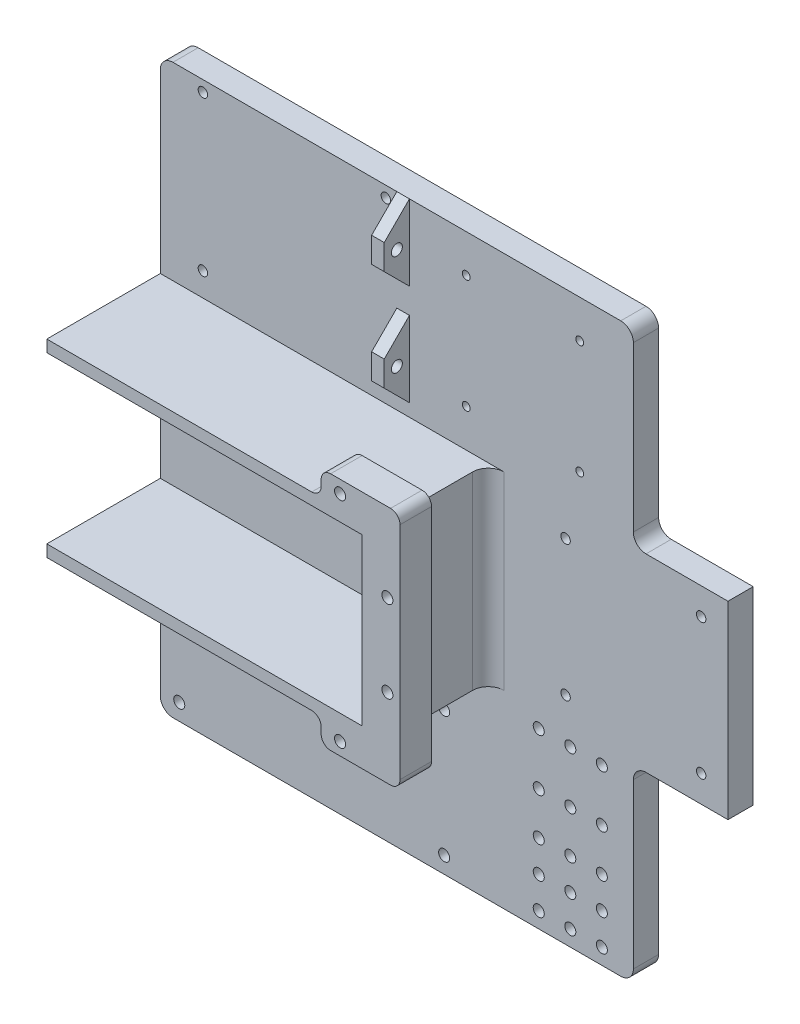
SolidWorks part; units mm, degrees
ref_plane "前视基准面" through (0, 0, 0) normal (0, 0, 1) x (1, 0, 0)
ref_plane "上视基准面" through (0, 0, 0) normal (0, 1, 0) x (1, 0, 0)
ref_plane "右视基准面" through (0, 0, 0) normal (1, 0, 0) x (0, 0, -1)
sketch "草图1" plane through (0, 0, 0) normal (0, 0, 1) x (1, 0, 0)
  line L1 (0, 0) -> (60, 0)
  line L2 (0, 0) -> (0, 60)
  line L3 (0, 60) -> (60, 60)
  line L4 (60, 0) -> (60, 60)
  dimension "D1" = 60
  dimension "D2" = 60
extrude "凸台-拉伸1" add sketch "草图1" along normal blind 8
sketch "草图2" plane through (0, 0, 0) normal (0, 0, -1) x (-1, 0, 0)
  line L0 (0, 0) -> (-60, 60)
  line L2 (-51.5, 8.5) -> (-8.5, 8.5)
  line L3 (-51.5, 8.5) -> (-51.5, 51.5)
  line L4 (-51.5, 51.5) -> (-8.5, 51.5)
  line L5 (-8.5, 8.5) -> (-8.5, 51.5)
  line L6 (-51.5, 8.5) -> (-8.5, 51.5) construction
  line L7 (-51.5, 51.5) -> (-8.5, 8.5) construction
  point P4 (-30, 30)
  dimension "D1" = 43
  dimension "D2" = 43
sketch "草图3" plane through (0, 0, 0) normal (0, 0, -1) x (-1, 0, 0)
  point P0 (-51.5, 51.5)
  point P3 (-8.5, 51.5)
  point P6 (-8.5, 8.5)
  point P9 (-51.5, 8.5)
hole_wizard "孔1" positions "草图3" profile "草图4" legacy end condition through all
sketch "草图4" plane through (51.5, 51.5, 0) normal (1, 0, 0) x (0, 1, 0)
  line L0 (0, 0) -> (0, 8)
  line L1 (0, 8) -> (1.5, 8)
  line L2 (1.5, 8) -> (1.5, 0)
  line L3 (1.5, 0) -> (0, 0)
  line L4 (0, 110) -> (0, -10) construction
  dimension "直径" = 3
  dimension "深度" = 8
sketch "草图5" plane through (0, 0, 0) normal (0, 0, -1) x (-1, 0, 0)
  point P0 (-51.5, 51.5)
  point P3 (-8.5, 51.5)
  point P6 (-8.5, 8.5)
  point P9 (-51.5, 8.5)
hole_wizard "孔2" positions "草图5" profile "草图6" legacy
sketch "草图6" plane through (51.5, 51.5, 0) normal (1, 0, 0) x (0, 1, 0)
  line L0 (0, 0) -> (0, 3)
  line L1 (0, 3) -> (2.5, 3)
  line L2 (2.5, 3) -> (2.5, 0)
  line L3 (2.5, 0) -> (0, 0)
  line L4 (0, 110) -> (0, -10) construction
  dimension "直径" = 5
  dimension "深度" = 3
sketch "草图8" plane through (0, 0, 8) normal (0, 0, 1) x (1, 0, 0)
  line L0 (60, 0) -> (60, 60) construction
  line L1 (60, -60) -> (-120, -60)
  line L2 (60, -60) -> (60, 120)
  line L3 (60, 120) -> (-120, 120)
  line L4 (-120, -60) -> (-120, 120)
  circle A0 centre (30, 30) radius 300
  dimension "D1" = 600
  dimension "D2" = 180
  dimension "D3" = 180
  dimension "D4" = 90
sketch "草图9" plane through (0, 0, 8) normal (0, 0, 1) x (1, 0, 0)
  line L1 (0, 60) -> (-25, 60)
  line L2 (0, 60) -> (0, 0)
  line L3 (0, 0) -> (-25, 0)
  line L4 (-25, 60) -> (-25, 0)
  dimension "D1" = 25
  dimension "D2" = 60
extrude "凸台-拉伸2" add sketch "草图9" against normal blind 8
sketch "草图10" plane through (0, 0, 8) normal (0, 0, 1) x (1, 0, 0)
  line L0 (-25, 0) -> (60, 0) construction
  line L1 (-20, 60) -> (-16, 60)
  line L2 (-20, 60) -> (-20, 0)
  line L3 (-20, 0) -> (-16, 0)
  line L4 (-16, 60) -> (-16, 0)
  line L5 (-25, 60) -> (-25, 0) construction
  dimension "D1" = 4
  dimension "D2" = 5
  dimension "D3" = 60
extrude "凸台-拉伸3" add sketch "草图10" along normal blind 20
fillet "圆角1" radius 5 1 edges at (-16, 30, 8)
sketch "草图11" plane through (0, 0, 8) normal (0, 0, 1) x (1, 0, 0)
  line L1 (-20, 60) -> (-120, 60)
  line L2 (-20, 60) -> (-20, 0)
  line L3 (-20, 0) -> (-120, 0)
  line L4 (-120, 60) -> (-120, 0)
  dimension "D1" = 100
  dimension "D2" = 60
extrude "凸台-拉伸4" add sketch "草图11" against normal blind 8
sketch "草图17" plane through (0, 0, 8) normal (0, 0, 1) x (1, 0, 0)
  line L1 (60, 60) -> (-120, 60)
  line L2 (60, 60) -> (60, 120)
  line L3 (60, 120) -> (-120, 120)
  line L4 (-120, 60) -> (-120, 120)
  line L5 (60, 0) -> (-120, 0)
  line L6 (60, 0) -> (60, -60)
  line L7 (60, -60) -> (-120, -60)
  line L8 (-120, 0) -> (-120, -60)
extrude "凸台-拉伸5" add sketch "草图17" against normal blind 8
sketch "草图12" plane through (0, 0, 8) normal (0, 0, 1) x (1, 0, 0)
  line L0 (-120, -60) -> (-120, 120) construction
  line L1 (-130, 120) -> (-45, 120)
  line L2 (-130, 120) -> (-130, 64)
  line L3 (-130, 64) -> (-45, 64)
  line L4 (-45, 120) -> (-45, 64)
  line L5 (-45, 92) -> (-130, 92)
  line L7 (-106.5, 116.5) -> (-48.5, 116.5)
  line L8 (-106.5, 116.5) -> (-106.5, 67.5)
  line L9 (-106.5, 67.5) -> (-48.5, 67.5)
  line L10 (-48.5, 116.5) -> (-48.5, 67.5)
  line L11 (60, 120) -> (-120, 120) construction
  point P8 (-120, 30)
  dimension "D1" = 56
  dimension "D2" = 85
  dimension "D3" = 3.5
  dimension "D4" = 3.5
  dimension "D5" = 58
  dimension "D6" = 49
  dimension "D7" = 10
sketch "草图13" plane through (0, 0, 8) normal (0, 0, 1) x (1, 0, 0)
  point P0 (-106.5, 116.5)
  point P3 (-48.5, 116.5)
  point P6 (-48.5, 67.5)
  point P9 (-106.5, 67.5)
hole_wizard "孔3" positions "草图13" profile "草图14" legacy end condition through all
sketch "草图14" plane through (-106.5, 116.5, 8) normal (1, 0, 0) x (0, -1, 0)
  line L0 (0, 0) -> (0, 8)
  line L1 (0, 8) -> (1.5, 8)
  line L2 (1.5, 8) -> (1.5, 0)
  line L3 (1.5, 0) -> (0, 0)
  line L4 (0, 110) -> (0, -10) construction
  dimension "直径" = 3
  dimension "深度" = 8
sketch "草图15" plane through (0, 0, 0) normal (0, 0, -1) x (-1, 0, 0)
  point P0 (48.5, 116.5)
  point P3 (106.5, 116.5)
  point P6 (106.5, 67.5)
  point P9 (48.5, 67.5)
hole_wizard "孔4" positions "草图15" profile "草图16" legacy
sketch "草图16" plane through (-48.5, 116.5, 0) normal (1, 0, 0) x (0, 1, 0)
  line L0 (0, 0) -> (0, 3)
  line L1 (0, 3) -> (2.5, 3)
  line L2 (2.5, 3) -> (2.5, 0)
  line L3 (2.5, 0) -> (0, 0)
  line L4 (0, 110) -> (0, -10) construction
  dimension "直径" = 5
  dimension "深度" = 3
sketch "草图18" plane through (0, 0, 8) normal (0, 0, 1) x (1, 0, 0)
  line L0 (-120, -60) -> (-120, 120) construction
  line L1 (-116, -11.5) -> (-25, -11.5)
  line L2 (-116, -11.5) -> (-116, -58)
  line L3 (-116, -58) -> (-25, -58)
  line L4 (-25, -11.5) -> (-25, -58)
  line L6 (60, -60) -> (-120, -60) construction
  line L7 (-114, -14.75) -> (-30, -14.75)
  line L8 (-114, -14.75) -> (-114, -54.75)
  line L9 (-114, -54.75) -> (-30, -54.75)
  line L10 (-30, -14.75) -> (-30, -54.75)
  dimension "D1" = 46.5
  dimension "D2" = 91
  dimension "D3" = 4
  dimension "D4" = 2
  dimension "D5" = 2
  dimension "D6" = 3.25
  dimension "D7" = 40
  dimension "D8" = 84
sketch "草图19" plane through (0, 0, 8) normal (0, 0, 1) x (1, 0, 0)
  point P0 (-114, -14.75)
  point P3 (-30, -14.75)
  point P6 (-30, -54.75)
  point P9 (-114, -54.75)
hole_wizard "孔5" positions "草图19" profile "草图20" legacy end condition through all
sketch "草图20" plane through (-114, -14.75, 8) normal (1, 0, 0) x (0, -1, 0)
  line L0 (0, 0) -> (0, 8)
  line L1 (0, 8) -> (1.75, 8)
  line L2 (1.75, 8) -> (1.75, 0)
  line L3 (1.75, 0) -> (0, 0)
  line L4 (0, 110) -> (0, -10) construction
  dimension "直径" = 3.5
  dimension "深度" = 8
sketch "草图21" plane through (0, 0, 0) normal (0, 0, -1) x (-1, 0, 0)
  point P0 (30, -14.75)
  point P3 (114, -14.75)
  point P6 (114, -54.75)
  point P9 (30, -54.75)
hole_wizard "孔6" positions "草图21" profile "草图22" legacy
sketch "草图22" plane through (-30, -14.75, 0) normal (1, 0, 0) x (0, 1, 0)
  line L0 (0, 0) -> (0, 4)
  line L1 (0, 4) -> (3.25, 4)
  line L2 (3.25, 4) -> (3.25, 0)
  line L3 (3.25, 0) -> (0, 0)
  line L4 (0, 110) -> (0, -10) construction
  dimension "直径" = 6.5
  dimension "深度" = 4
sketch "草图24" plane through (0, 0, 8) normal (0, 0, 1) x (1, 0, 0)
  line L0 (-120, -60) -> (-120, 120) construction
  line L1 (-120, 60) -> (-20, 60)
  line L2 (-120, 60) -> (-120, 0)
  line L3 (-120, 0) -> (-20, 0)
  line L4 (-20, 60) -> (-20, 0)
  line L6 (-20, 60) -> (-20, 0) construction
  line L7 (-16, 60) -> (-20, 60) construction
  point P6 (-120, 30)
  dimension "D1" = 60
sketch "草图25" plane through (0, 0, 8) normal (0, 0, 1) x (1, 0, 0)
  line L10 (-120, 0) -> (-16, 0)
  line L11 (-120, 0) -> (-120, 60)
  line L12 (-120, 60) -> (-16, 60)
  line L13 (-16, 0) -> (-16, 60)
extrude "凸台-拉伸7" add sketch "草图25" along normal blind 36
sketch "草图26" plane through (0, 0, 44) normal (0, 0, 1) x (1, 0, 0)
  line L0 (-120, -60) -> (-120, 120) construction
  line L1 (-120, 56.25) -> (-20, 56.25)
  line L2 (-120, 56.25) -> (-120, 3.75)
  line L3 (-120, 3.75) -> (-20, 3.75)
  line L4 (-20, 56.25) -> (-20, 3.75)
  line L5 (-16, 0) -> (-16, 60) construction
  point P8 (-120, 30)
  dimension "D1" = 52.5
  dimension "D2" = 4
extrude "切除-拉伸1" cut sketch "草图26" against normal blind 36
sketch "草图27" plane through (0, 0, 44) normal (0, 0, 1) x (1, 0, 0)
  line L1 (-16, 60) -> (-8, 60)
  line L2 (-16, 60) -> (-16, 0)
  line L3 (-16, 0) -> (-8, 0)
  line L4 (-8, 60) -> (-8, 0)
  line L5 (-8, 0) -> (-33, 0)
  line L6 (-8, 0) -> (-8, -8)
  line L7 (-8, -8) -> (-33, -8)
  line L8 (-33, 0) -> (-33, -8)
  line L9 (-8, 60) -> (-33, 60)
  line L10 (-8, 60) -> (-8, 68)
  line L11 (-8, 68) -> (-33, 68)
  line L12 (-33, 60) -> (-33, 68)
  line M8 (-120, 0) -> (-16, 0)
  line M9 (-16, 0) -> (-16, 60)
  line M10 (-16, 60) -> (-120, 60)
  dimension "D1" = 8
  dimension "D2" = 60
  dimension "D3" = 8
  dimension "D4" = 25
  dimension "D5" = 25
  dimension "D6" = 8
extrude "凸台-拉伸8" add sketch "草图27" against normal blind 10 contours L12 L1 L10 L11 M10 | L4 L1 L3 M9 | L8 L7 L6 L3 M8
sketch "草图28" plane through (0, 0, 44) normal (0, 0, 1) x (1, 0, 0)
  line L0 (-33, 64) -> (-8, 64)
  line L1 (-33, 60) -> (-33, 68) construction
  line L2 (-8, -8) -> (-8, 68) construction
  line L3 (-33, -4) -> (-8, -4)
  line L4 (-33, 0) -> (-33, -8) construction
  line L5 (-12, -8) -> (-12, 68)
  line L6 (-8, -8) -> (-33, -8) construction
  line L7 (-8, 68) -> (-33, 68) construction
  point P16 (-27, 64)
  point P17 (-27, -4)
  point P18 (-12, 43)
  point P19 (-12, 17)
  dimension "D1" = 4
  dimension "D2" = 6
  dimension "D3" = 6
  dimension "D4" = 25
  dimension "D5" = 25
sketch "草图29" plane through (0, 0, 44) normal (0, 0, 1) x (1, 0, 0)
  point P0 (-27, 64)
  point P3 (-12, 43)
  point P6 (-12, 17)
  point P9 (-27, -4)
hole_wizard "孔7" positions "草图29" profile "草图30" legacy
sketch "草图30" plane through (-27, 64, 44) normal (1, 0, 0) x (0, -1, 0)
  line L0 (0, 0) -> (0, 10)
  line L1 (0, 10) -> (1.75, 10)
  line L2 (1.75, 10) -> (1.75, 0)
  line L3 (1.75, 0) -> (0, 0)
  line L4 (0, 110) -> (0, -10) construction
  dimension "直径" = 3.5
  dimension "深度" = 10
fillet "圆角2" radius 3 6 edges at (-33, 0, 39) (-33, -8, 39) (-8, -8, 39) (-8, 68, 39) (-33, 68, 39) (-33, 60, 39)
sketch "草图31" plane through (0, 0, 8) normal (0, 0, 1) x (1, 0, 0)
  line L0 (60, 120) -> (-120, 120) construction
  line L1 (-25, 120) -> (15, 120)
  line L2 (-25, 120) -> (-25, 64)
  line L3 (-25, 64) -> (15, 64)
  line L4 (15, 120) -> (15, 64)
  line L5 (-45, 120) -> (-45, 64) construction
  line L7 (-23, 108) -> (13, 108)
  line L8 (-23, 108) -> (-23, 72)
  line L9 (-23, 72) -> (13, 72)
  line L10 (13, 108) -> (13, 72)
  point P8 (-5, 64)
  point P14 (15, 64)
  point P15 (-5, 154.7573)
  dimension "D1" = 56
  dimension "D2" = 20
  dimension "D3" = 40
  dimension "D4" = 8
  dimension "D5" = 2
  dimension "D6" = 36
  dimension "D7" = 36
sketch "草图32" plane through (0, 0, 8) normal (0, 0, 1) x (1, 0, 0)
  line L1 (0, 0) -> (60, 0)
  line L2 (0, 0) -> (0, 60)
  line L3 (0, 60) -> (60, 60)
  line L4 (60, 0) -> (60, 60)
sketch "草图33" plane through (0, 0, 8) normal (0, 0, 1) x (1, 0, 0)
  point P0 (13, 108)
  point P3 (13, 72)
  point P6 (-23, 72)
  point P9 (-23, 108)
hole_wizard "孔8" positions "草图33" profile "草图34" legacy end condition through all
sketch "草图34" plane through (13, 108, 8) normal (1, 0, 0) x (0, -1, 0)
  line L0 (0, 0) -> (0, 8)
  line L1 (0, 8) -> (1.25, 8)
  line L2 (1.25, 8) -> (1.25, 0)
  line L3 (1.25, 0) -> (0, 0)
  line L4 (0, 110) -> (0, -10) construction
  dimension "直径" = 2.5
  dimension "深度" = 8
sketch "草图35" plane through (0, 0, 0) normal (0, 0, -1) x (-1, 0, 0)
  point P0 (-13, 108)
  point P3 (23, 108)
  point P6 (23, 72)
  point P9 (-13, 72)
hole_wizard "孔9" positions "草图35" profile "草图36" legacy
sketch "草图36" plane through (13, 108, 0) normal (1, 0, 0) x (0, 1, 0)
  line L0 (0, 0) -> (0, 4)
  line L1 (0, 4) -> (2.1, 4)
  line L2 (2.1, 4) -> (2.1, 0)
  line L3 (2.1, 0) -> (0, 0)
  line L4 (0, 110) -> (0, -10) construction
  dimension "直径" = 4.2
  dimension "深度" = 4
sketch "草图37" plane through (0, 0, 8) normal (0, 0, 1) x (1, 0, 0)
  line L0 (0, 60) -> (60, 60) construction
  line L1 (60, 120) -> (30, 120)
  line L2 (60, 120) -> (60, 60)
  line L3 (60, 60) -> (30, 60)
  line L4 (30, 120) -> (30, 60)
  line L5 (0, 0) -> (60, 0) construction
  line L6 (60, -60) -> (30, -60)
  line L7 (60, -60) -> (60, 0)
  line L8 (60, 0) -> (30, 0)
  line L9 (30, -60) -> (30, 0)
  dimension "D1" = 30
  dimension "D2" = 30
extrude "切除-拉伸2" cut sketch "草图37" against normal through all
fillet "圆角3" radius 4 6 edges at (-120, 120, 4) (-120, -60, 4) (30, -60, 4) (30, 0, 4) (30, 120, 4) (30, 60, 4)
sketch "草图38" plane through (0, 0, 8) normal (0, 0, 1) x (1, 0, 0)
  line L0 (0, 0) -> (60, 0) construction
  line L1 (30, 0) -> (-10, 0)
  line L2 (30, 0) -> (30, -60)
  line L3 (30, -60) -> (-10, -60)
  line L4 (-10, 0) -> (-10, -60)
  line L5 (60, -60) -> (-120, -60) construction
  line L7 (20, 0) -> (20, -60)
  line L8 (0, 0) -> (0, -60)
  line L9 (10, 0) -> (10, -60)
  point P14 (0, -55)
  point P15 (10, -55)
  point P16 (20, -55)
  dimension "D1" = 40
  dimension "D2" = 10
  dimension "D3" = 10
  dimension "D4" = 5
  dimension "D5" = 5
  dimension "D6" = 5
sketch "草图39" plane through (0, 0, 8) normal (0, 0, 1) x (1, 0, 0)
  point P0 (0, -55)
  point P3 (10, -55)
  point P6 (20, -55)
hole_wizard "孔10" positions "草图39" profile "草图40" legacy end condition through all
sketch "草图40" plane through (0, -55, 8) normal (1, 0, 0) x (0, -1, 0)
  line L0 (0, 0) -> (0, 8)
  line L1 (0, 8) -> (1.75, 8)
  line L2 (1.75, 8) -> (1.75, 0)
  line L3 (1.75, 0) -> (0, 0)
  line L4 (0, 110) -> (0, -10) construction
  dimension "直径" = 3.5
  dimension "深度" = 8
pattern_linear "阵列(线性)1" count 6 spacing 10 along (0, 1, 0) skipping (3, 0), (4, 0) of "孔10"
sketch "草图41" plane through (0, 0, 0) normal (0, 0, -1) x (-1, 0, 0)
  point P0 (0, -55)
  point P3 (-10, -55)
  point P6 (-20, -55)
hole_wizard "孔11" positions "草图41" profile "草图42" legacy
sketch "草图42" plane through (0, -55, 0) normal (1, 0, 0) x (0, 1, 0)
  line L0 (0, 0) -> (0, 4)
  line L1 (0, 4) -> (3, 4)
  line L2 (3, 4) -> (3, 0)
  line L3 (3, 0) -> (0, 0)
  line L4 (0, 110) -> (0, -10) construction
  dimension "直径" = 6
  dimension "深度" = 4
pattern_linear "阵列(线性)2" count 6 spacing 10 along (0, 1, 0) skipping (3, 0), (4, 0) of "孔11"
sketch "草图43" plane through (0, 0, 8) normal (0, 0, 1) x (1, 0, 0)
  line L0 (0, -55) -> (0, -21.5)
  line L1 (0, 0) -> (0, -60) construction
  line L2 (0, -21.5) -> (20, -21.5)
  line L3 (20, 0) -> (20, -60) construction
  dimension "D1" = 33.5
sketch "草图44" plane through (0, 0, 8) normal (0, 0, 1) x (1, 0, 0)
  line L0 (0, -21.5) -> (20, -21.5) construction
  point P0 (0, -21.5)
  point P3 (10, -21.5)
  point P7 (20, -21.5)
hole_wizard "孔12" positions "草图44" profile "草图45" legacy end condition through all
sketch "草图45" plane through (0, -21.5, 8) normal (1, 0, 0) x (0, -1, 0)
  line L0 (0, 0) -> (0, 8)
  line L1 (0, 8) -> (1.75, 8)
  line L2 (1.75, 8) -> (1.75, 0)
  line L3 (1.75, 0) -> (0, 0)
  line L4 (0, 110) -> (0, -10) construction
  dimension "直径" = 3.5
  dimension "深度" = 8
hole_wizard "孔13" positions "草图46" profile "草图47" legacy
sketch "草图46" plane through (0, 0, 0) normal (0, 0, -1) x (-1, 0, 0)
  point P0 (-20, -21.5)
  point P3 (-10, -21.5)
  point P6 (0, -21.5)
sketch "草图47" plane through (20, -21.5, 0) normal (1, 0, 0) x (0, 1, 0)
  line L0 (0, 0) -> (0, 4)
  line L1 (0, 4) -> (3, 4)
  line L2 (3, 4) -> (3, 0)
  line L3 (3, 0) -> (0, 0)
  line L4 (0, 110) -> (0, -10) construction
  dimension "直径" = 6
  dimension "深度" = 4
sketch "草图48" plane through (0, 0, 8) normal (0, 0, 1) x (1, 0, 0)
  line L0 (-45, 92) -> (-45, 108)
  line L1 (-45, 120) -> (-45, 64) construction
  line L2 (-45, 92) -> (-45, 76)
  line L4 (-45, 104) -> (-41, 104)
  line L5 (-45, 104) -> (-45, 112)
  line L6 (-45, 112) -> (-41, 112)
  line L7 (-41, 104) -> (-41, 112)
  line L8 (-45, 80) -> (-41, 80)
  line L9 (-45, 80) -> (-45, 72)
  line L10 (-45, 72) -> (-41, 72)
  line L11 (-41, 80) -> (-41, 72)
  dimension "D1" = 16
  dimension "D2" = 16
  dimension "D3" = 4
  dimension "D4" = 8
  dimension "D5" = 4
  dimension "D6" = 8
  dimension "D7" = 4
  dimension "D8" = 4
extrude "凸台-拉伸9" add sketch "草图48" along normal blind 8 contours L4 L7 L6 L5 L0 | L11 L8 L2 L9 L10
sketch "草图49" plane through (-41, 0, 0) normal (1, 0, 0) x (0, 0, -1)
  line L0 (-16, 112) -> (-8, 120)
  line L1 (-8, 330) -> (-8, -270) construction
  line L2 (-8, 120) -> (-8, 112)
  line L3 (-8, 112) -> (-16, 112)
  line L4 (-16, 104) -> (-8, 96)
  line L5 (-8, 96) -> (-8, 104)
  line L6 (-16, 104) -> (-8, 104) construction
  line L7 (-8, 104) -> (-16, 104)
  line L8 (-16, 80) -> (-8, 88)
  line L9 (-8, 88) -> (-8, 80)
  line L10 (-8, 80) -> (-16, 80)
  line L11 (-16, 72) -> (-8, 72)
  line L12 (-8, 72) -> (-8, 64)
  line L13 (-8, 64) -> (-16, 72)
  dimension "D1" = 45
  dimension "D2" = 45
  dimension "D3" = 45
  dimension "D4" = 45
extrude "凸台-拉伸10" add sketch "草图49" against normal blind 4
sketch "草图50" plane through (-41, 0, 0) normal (1, 0, 0) x (0, 0, -1)
  line L0 (-16, 108) -> (-8, 108)
  line L1 (-16, 104) -> (-16, 112) construction
  line L2 (-8, 330) -> (-8, -270) construction
  line L3 (-16, 76) -> (-8, 76)
  line L4 (-16, 80) -> (-16, 72) construction
  point P10 (-12, 108)
  point P11 (-12, 76)
sketch "草图51" plane through (-41, 0, 0) normal (1, 0, 0) x (0, 0, -1)
  line L0 (-16, 76) -> (-8, 76) construction
  point P0 (-12, 108)
  point P3 (-12, 76)
hole_wizard "孔14" positions "草图51" profile "草图52" legacy end condition through all
sketch "草图52" plane through (-41, 108, 12) normal (0, 1, 0) x (0, 0, -1)
  line L0 (0, 0) -> (0, 79)
  line L1 (0, 79) -> (1.75, 79)
  line L2 (1.75, 79) -> (1.75, 0)
  line L3 (1.75, 0) -> (0, 0)
  line L4 (0, 110) -> (0, -10) construction
  dimension "直径" = 3.5
  dimension "深度" = 79
